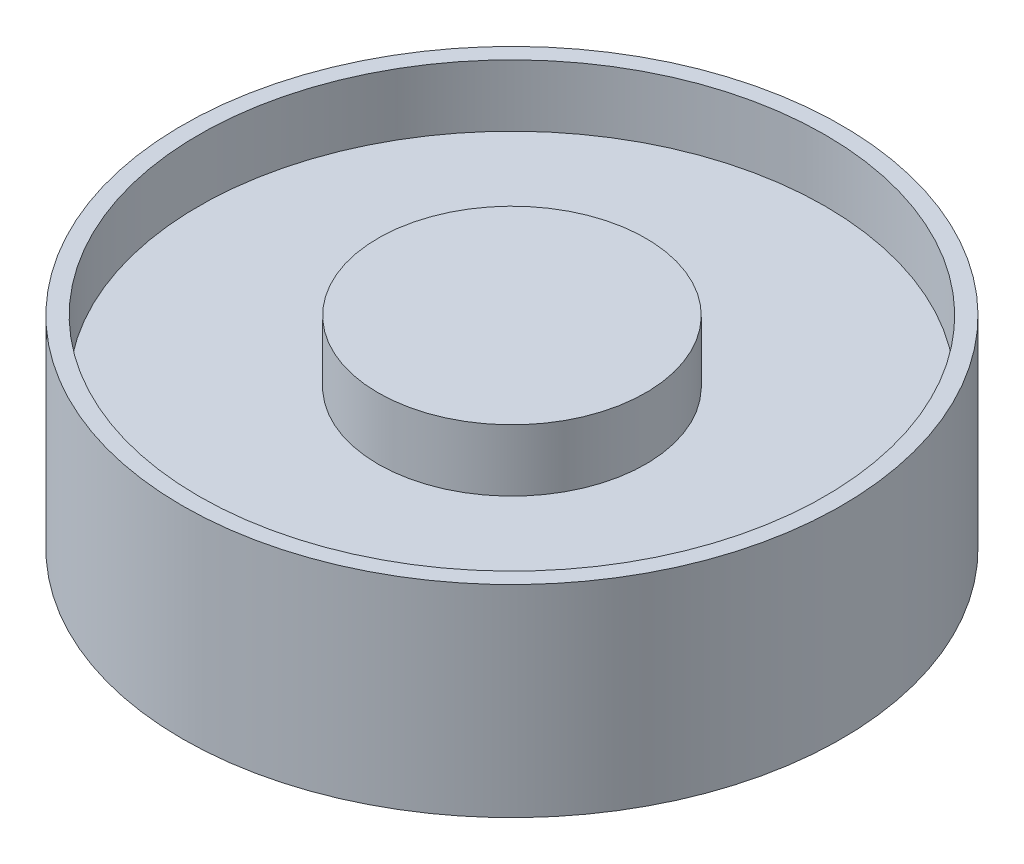
SolidWorks part; units mm, degrees
ref_plane "Front Plane" through (0, 0, 0) normal (0, 0, 1) x (1, 0, 0)
ref_plane "Top Plane" through (0, 0, 0) normal (0, 1, 0) x (1, 0, 0)
ref_plane "Right Plane" through (0, 0, 0) normal (1, 0, 0) x (0, 0, -1)
sketch "Sketch1" plane through (0, 0, 0) normal (0, 1, 0) x (1, 0, 0)
  circle A0 centre (0, 0) radius 8
  dimension "D1" = 16
extrude "Boss-Extrude1" add sketch "Sketch1" along normal blind 3.4
sketch "Sketch2" plane through (0, 3.4, 0) normal (0, 1, 0) x (1, 0, 0)
  circle A0 centre (0, 0) radius 8
  circle A1 centre (0, 0) radius 7.6
  circle A2 centre (0, 0) radius 3.25
  circle M1 centre (0, 0) radius 8
  dimension "D1" = 15.2
  dimension "D2" = 16
  dimension "D3" = 6.5
extrude "Boss-Extrude2" add sketch "Sketch2" along normal blind 1.5 contours A1 M1 | A2
